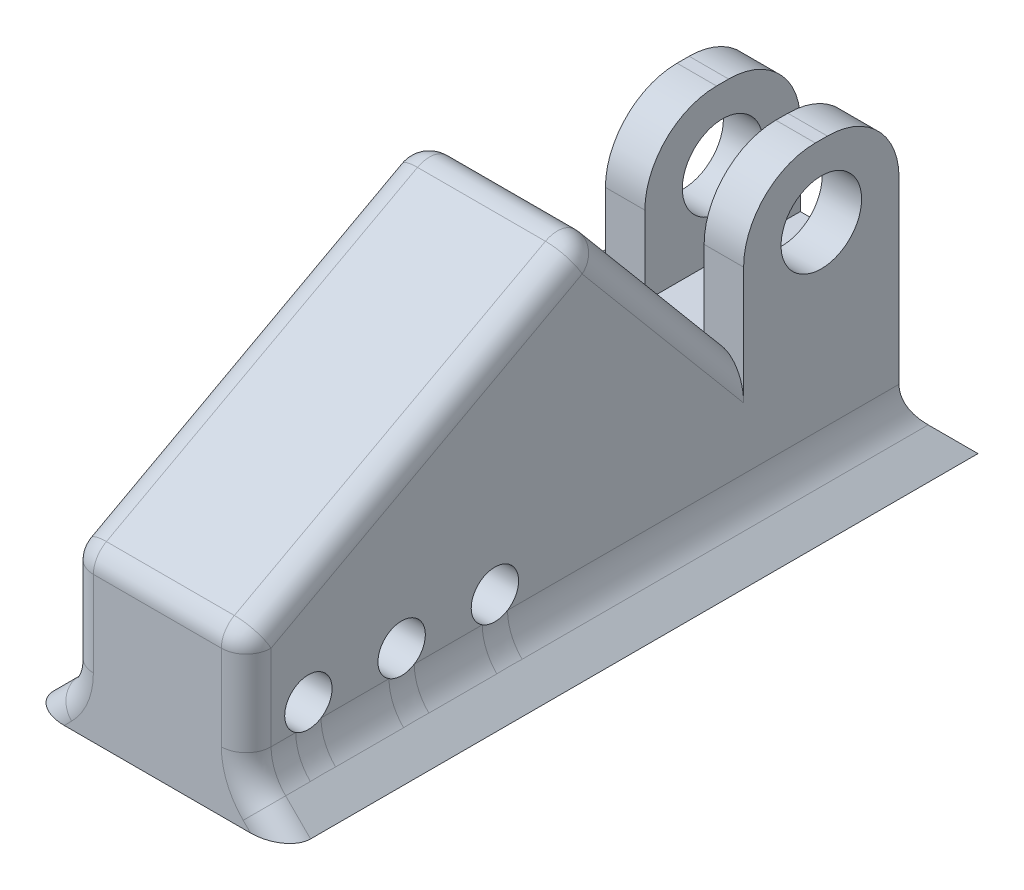
SolidWorks part; units mm, degrees
ref_plane "Front Plane" through (0, 0, 0) normal (0, 0, 1) x (1, 0, 0)
ref_plane "Top Plane" through (0, 0, 0) normal (0, 1, 0) x (1, 0, 0)
ref_plane "Right Plane" through (0, 0, 0) normal (1, 0, 0) x (0, 0, -1)
sketch "Sketch1" plane through (0, 0, 0) normal (0, 0, 1) x (1, 0, 0)
  line L1 (-14.29, -25) -> (14.29, -25)
  line L2 (-14.29, -25) -> (-14.29, 25)
  line L3 (-14.29, 25) -> (14.29, 25)
  line L4 (14.29, -25) -> (14.29, 25)
  line L5 (-14.29, -25) -> (14.29, 25) construction
  line L6 (-14.29, 25) -> (14.29, -25) construction
  point P0 (0, 0)
  dimension "D1" = 50
  dimension "D2" = 28.58
extrude "Boss-Extrude1" add sketch "Sketch1" along normal mid plane 25
sketch "Sketch2" plane through (0, 0, 12.5) normal (0, 0, 1) x (-1, 0, 0)
  line L1 (-7.94, -0.775) -> (1.59, -0.775)
  line L2 (-7.94, -0.775) -> (-7.94, -25)
  line L3 (-7.94, -25) -> (1.59, -25)
  line L4 (1.59, -0.775) -> (1.59, -25)
  line L5 (7.94, -0.775) -> (14.29, -0.775)
  line L6 (7.94, -0.775) -> (7.94, -25)
  line L7 (7.94, -25) -> (14.29, -25)
  line L8 (14.29, -0.775) -> (14.29, -25)
  line L10 (-14.29, -25) -> (14.29, -25) construction
  line L11 (14.29, -25) -> (14.29, 25) construction
  line L12 (-14.29, 25) -> (-14.29, -25) construction
  dimension "D1" = 6.35
  dimension "D2" = 6.35
  dimension "D3" = 24.225
  dimension "D4" = 6.35
extrude "Cut-Extrude1" cut sketch "Sketch2" against normal through all
fillet "Fillet1" radius 11.53 4 edges at (-4.765, 25, -12.5) (-4.765, 25, 12.5) (11.115, 25, 12.5) (11.115, 25, -12.5)
sketch "Sketch3" plane through (14.29, 0, 0) normal (1, 0, 0) x (0, 0, -1)
  line L0 (-11.4063, 13.47) -> (20.1617, 13.47) construction
  line L1 (0, 37.5) -> (0, -49962.5) construction
  line L2 (-0.97, 25) -> (0.97, 25) construction
  circle A0 centre (0, 13.47) radius 6.477
  point P9 (0, 25)
  dimension "D1" = 12.954
extrude "Cut-Extrude2" cut sketch "Sketch3" against normal through all
sketch "Sketch4" plane through (14.29, 0, 0) normal (1, 0, 0) x (0, 0, -1)
  line L0 (-15.659, -25) -> (49984.341, -25) construction
  line L2 (-12.5, -25) -> (12.5, -25) construction
  line L3 (18.85, -25) -> (12.5, -18.65)
  line L4 (12.5, -25) -> (12.5, 13.47) construction
  line L5 (12.5, -18.65) -> (12.5, -25)
  line L6 (12.5, -25) -> (18.85, -25)
  dimension "D1" = 6.35
  dimension "D2" = 45
extrude "Boss-Extrude2" add sketch "Sketch4" against normal up to surface (28.58 mm away) up to face at (-14.29, -12.1125, 0)
sketch "Sketch5" plane through (0, 0, 12.5) normal (0, 0, 1) x (1, 0, 0)
  line L0 (-1.59, 0.775) -> (7.94, 0.775) construction
  line L1 (-14.29, -25) -> (14.29, -25)
  line L2 (-14.29, -25) -> (-14.29, 0.775)
  line L3 (-14.29, 0.775) -> (14.29, 0.775)
  line L4 (14.29, -25) -> (14.29, 0.775)
  line L5 (14.29, -25) -> (14.29, 13.47) construction
extrude "Boss-Extrude3" add sketch "Sketch5" along normal blind 80
sketch "Sketch6" plane through (14.29, 0, 0) normal (1, 0, 0) x (0, 0, -1)
  line L0 (-82.5, 0.775) -> (-82.5, -27.4392) construction
  line L1 (-92.5, -25) -> (-92.5, 0.775) construction
  line L2 (-39.7474, -12.1125) -> (-45.2025, -12.1125) construction
  circle A0 centre (-82.5, -12.1125) radius 3.81
  circle A1 centre (-67.5, -12.1125) radius 3.81
  circle A2 centre (-52.5, -12.1125) radius 3.81
  dimension "D1" = 7.62
  dimension "D2" = 10
  dimension "D3" = 15
  dimension "D4" = 15
extrude "Cut-Extrude3" cut sketch "Sketch6" against normal through all both and the other way through all
sketch "Sketch7" plane through (0, 0, -12.5) normal (0, 0, -1) x (-1, 0, 0)
  line L0 (-14.29, -25) -> (-20.64, -25)
  line L1 (-20.64, -25) -> (-14.29, -18.65)
  line L2 (-14.29, -18.65) -> (-14.29, 13.47) construction
  line L3 (14.29, -25) -> (-14.29, -25) construction
  line L4 (-14.29, -25) -> (-14.29, -18.65) construction
  line L5 (-14.29, -18.65) -> (-14.29, -25)
  dimension "D1" = 45
  dimension "D2" = 6.35
extrude "Boss-Extrude4" add sketch "Sketch7" against normal up to surface and the other way up to surface up to face at (0, -12.1125, 92.5) other way up to face at (0, -21.825, -15.675)
mirror "Mirror2" about plane through (0, 0, 0) normal (1, 0, 0) of "Boss-Extrude4"
hole_wizard "Trous de centrage Ø5.0mm1" positions "Sketch9" profile "Sketch11" hole size "Ø5.0" standard "Ansi Metric"
sketch "Sketch9" plane through (0, -25, 0) normal (0, -1, 0) x (-1, 0, 0)
  point P0 (-7.5, 0.5343)
  point P3 (7.5, 0.5343)
  point P6 (7.5, -14.4657)
  point P9 (-7.5, -14.4657)
  point P12 (-7.5, -29.4657)
  point P14 (7.5, -29.4657)
  point P16 (7.5, -44.4657)
  point P18 (-7.5, -44.4657)
  point P21 (0, 0)
  point P22 (0, 0)
  point P23 (0, 0)
  point P24 (0, 0)
  dimension "D1" = 15
  dimension "D2" = 15
  dimension "D3" = 15
  dimension "D4" = 15
sketch "Sketch11" plane through (7.5, -25, -0.5343) normal (1, 0, 0) x (0, 0, -1)
  line L0 (0, 0) -> (0, 11.5022)
  line L1 (0, 11.5022) -> (2.5, 10)
  line L2 (2.5, 10) -> (2.5, 0)
  line L5 (2.5, 0) -> (0, 0)
  line L10 (0, 11.5022) -> (-2.5, 10) construction
  line L11 (0, -6.35) -> (0, 107.95) construction
  dimension "Hole Dia." = 5
  dimension "Hole Depth" = 10
  dimension "Drill Angle" = 118
sketch "Esquisse1" plane through (14.29, 0, 0) normal (1, 0, 0) x (0, 0, -1)
  line L1 (-37.5, 30.5688) -> (-12.5, 0.775)
  line L2 (-12.5, 0.775) -> (-92.5, 0.775)
  line L5 (-92.5, 0.775) -> (-37.5, 30.5688)
  dimension "D1" = 50
  dimension "D2" = 25
extrude "Boss.-Extru.1" add sketch "Esquisse1" against normal up to surface (28.58 mm away) up to face at (-14.29, -12.1125, 48.69)
fillet "Fillet2" radius 8 3 edges at (-14.29, -18.65, 40) (14.29, -18.65, 40) (0, -18.65, -12.5)
fillet "Fillet4" radius 4 13 edges at (-14.29, 0.775, 0) (-18.6366, -22.9966, 92.5) (-14.899, -18.3978, 92.5) (18.6366, -22.9966, 92.5) (14.899, -18.3978, 92.5) (-14.29, -7.2806, 92.5) (14.29, -7.2806, 92.5) (-14.29, 15.6719, 25) (14.29, 15.6719, 25) (0, 0.775, 92.5) (-14.29, 15.6719, 65) (14.29, 15.6719, 65) (0, 30.5688, 37.5)
